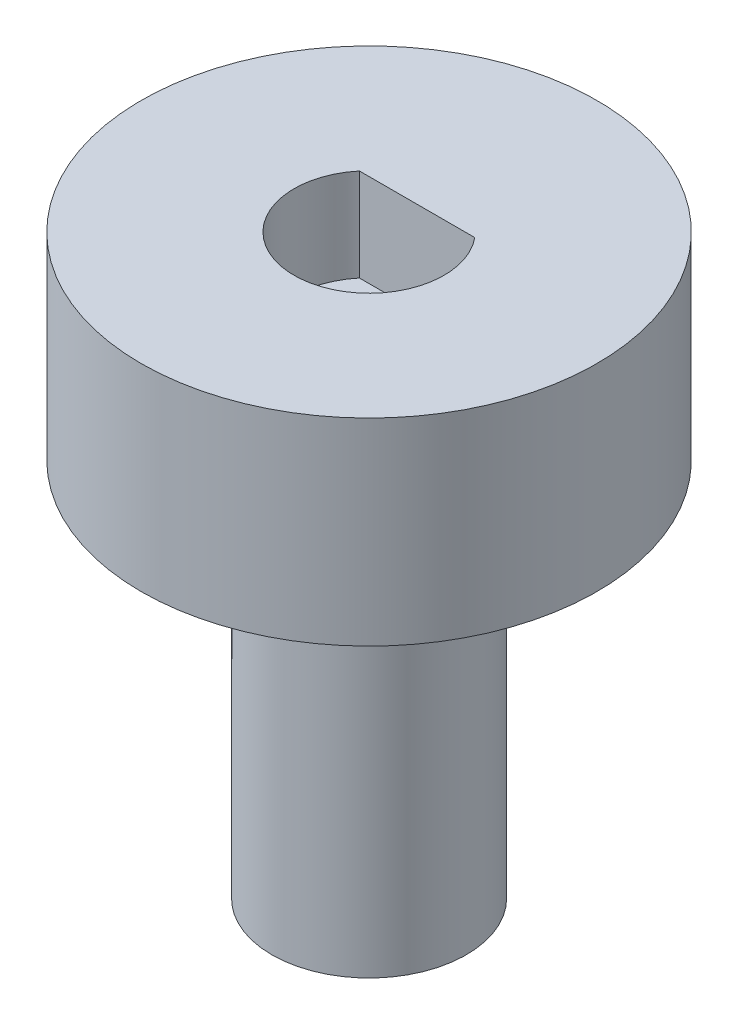
SolidWorks part; units mm, degrees
ref_plane "Front Plane" through (0, 0, 0) normal (0, 0, 1) x (1, 0, 0)
ref_plane "Top Plane" through (0, 0, 0) normal (0, 1, 0) x (1, 0, 0)
ref_plane "Right Plane" through (0, 0, 0) normal (1, 0, 0) x (0, 0, -1)
sketch "Sketch2" plane through (0, 0, 0) normal (0, 1, 0) x (1, 0, 0)
  circle A0 centre (0, 0) radius 4.066
  dimension "D1" = 8.132
extrude "Boss-Extrude1" add sketch "Sketch2" along normal blind 15.875
sketch "Sketch3" plane through (0, 15.875, 0) normal (0, 1, 0) x (1, 0, 0)
  circle A0 centre (0, 0) radius 9.525
  dimension "D1" = 19.05
extrude "Boss-Extrude2" add sketch "Sketch3" along normal blind 8.255
sketch "Sketch4" plane through (0, 24.13, 0) normal (0, 1, 0) x (1, 0, 0)
  line L0 (-2.4103, 2.0076) -> (2.4103, 2.0076)
  arc A0 (-2.4103, 2.0076) -> (2.4103, 2.0076) centre (0, 0) ccw
  dimension "D1" = 6.2738
extrude "Cut-Extrude1" cut sketch "Sketch4" against normal blind 3.875
